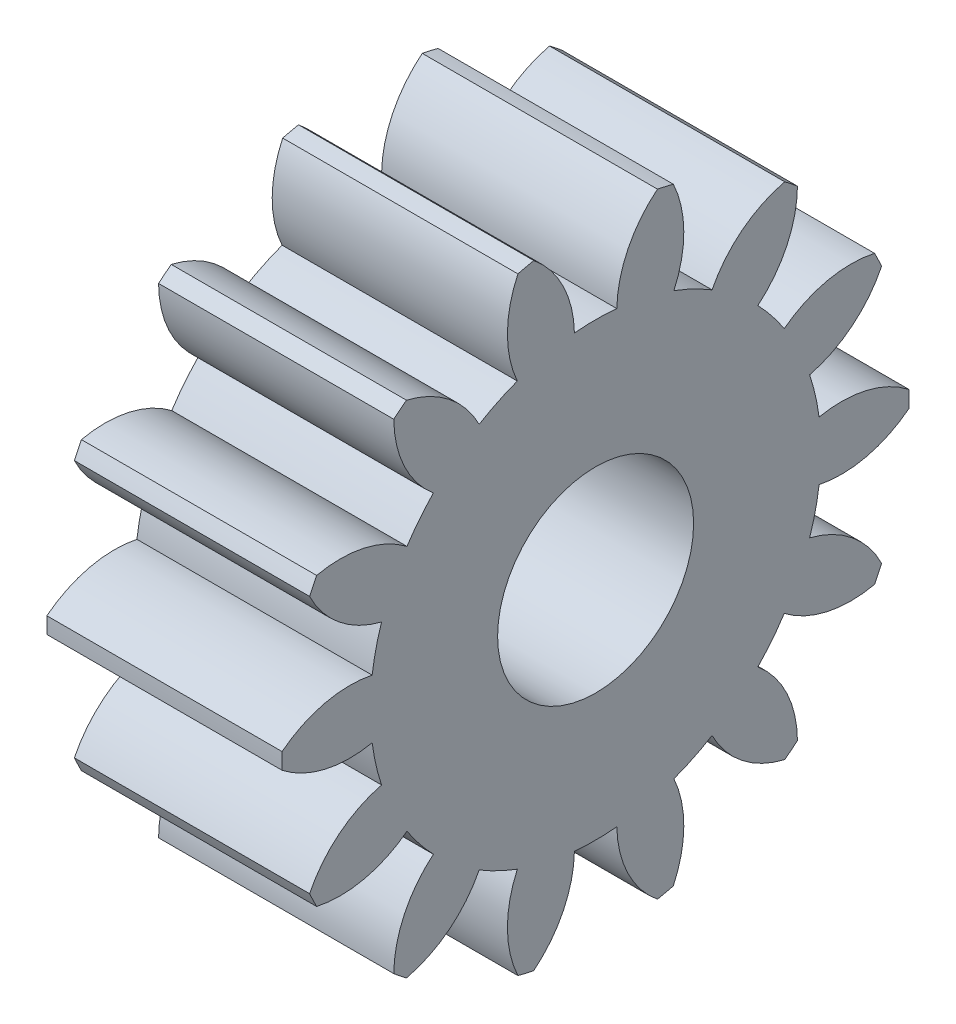
SolidWorks part; units mm, degrees
ref_plane "Plane1" through (0, 0, 0) normal (0, 0, 1) x (1, 0, 0)
ref_plane "Plane2" through (0, 0, 0) normal (0, 1, 0) x (1, 0, 0)
ref_plane "Plane3" through (0, 0, 0) normal (1, 0, 0) x (0, 0, -1)
other "Configuration Table"
sketch "HoldingSke" plane through (0, 0, 0) normal (0, 1, 0) x (1, 0, 0)
  line L0 (0, 0) -> (0.9703, -0.2419)
  line L1 (-15, 0) -> (100, 0) construction
  line L2 (0, 0) -> (-2.1039, 2.3779)
  line L3 (0, 0) -> (-11.863, 4.5341)
  line L4 (0, 0) -> (8.3795, 2.0892)
  line L5 (0, 0) -> (-9.3695, -3.4946)
  line L6 (0, 0) -> (-4.9738, -3.3558)
  line L7 (-2.1039, 2.3779) -> (0.0486, 12.1435)
  line L8 (-76.2, 54.61) -> (-75.3, 54.61)
  line L9 (-71.009, 38.7566) -> (-53.1078, 45.2721)
  line L10 (-76.2, 71.12) -> (104.1128, 71.12)
  line L11 (0, 0) -> (-6, 0)
  line L12 (-76.2, 101.6) -> (-76.162, 101.6)
  line L13 (24.9733, 27.94) -> (52.9518, 28.4284)
  line L14 (24.9733, 27.94) -> (24.9743, 27.94)
  line L15 (24.9733, 27.94) -> (100.4006, 29.5858)
  line L16 (-63.627, -1) -> (-12.827, -1)
  circle A0 centre (0, 0) radius 2.5
  circle A1 centre (0, 0) radius 5.749
  circle A2 centre (0, 0) radius 37.5
  circle A3 centre (0, 0) radius 2.5
  dimension "MHD" = 11.498
  dimension "Hub_dia" = 75
  dimension "Bore" = 5
  dimension "MBD" = 5
  dimension "Num_teeth" = 14
  dimension "Pitch" = 1
  dimension "Overall_len" = 10
  dimension "Show_teeth" = 14
  dimension "Thickness" = 6
  dimension "OAL" = 10.0001
  dimension "T_dim" = 0.9
  dimension "Ap" = 20
  dimension "H" = 19.05
  dimension "Pitch_radius" = 180.3128
  dimension "Width" = 6
  dimension "Backlash" = 0.038
  dimension "Addendum_fac" = 1
  dimension "Dedendum_fac" = 1.25
  dimension "Clearance_fac" = 0.25
  dimension "Dedendum_add" = 0.001
  dimension "Module" = 1
sketch "BasProSke" plane through (0, 0, 0) normal (0, 1, 0) x (1, 0, 0)
  line L0 (-10, 0) -> (60, 0) construction
  line L1 (0, 0) -> (0, 8)
  line L2 (0, 0) -> (6, 0)
  line L3 (6, 0) -> (6, 8)
  line L4 (6, 8) -> (0, 8)
  dimension "Thickness" = 6
  dimension "Diameter" = 16
revolve "Base-Revolve" add sketch "BasProSke" angle 360 about L0
sketch "TooCutSke" plane through (0, 0, 0) normal (1, 0, 0) x (0, 0, -1)
  line L1 (0, 0) -> (0, 107) construction
  line L2 (0, 0) -> (-0.8502, 6.9482) construction
  line L3 (0, 0) -> (-3.0989, 13.5772) construction
  line L4 (-0.8502, 6.9482) -> (-1.5494, 6.7886) construction
  arc A0 (0.5404, 5.7235) -> (-0.5404, 5.7235) centre (0, 0) ccw
  arc A1 (1.6036, 7.8636) -> (-1.6036, 7.8636) centre (0, 0) ccw
  circle A2 centre (0, 0) radius 7 construction
  circle A3 centre (0, 0) radius 6.5778 construction
  arc A4 (-0.5404, 5.7235) -> (-1.6036, 7.8636) centre (-3.3398, 5.6669) ccw
  arc A5 (1.6036, 7.8636) -> (0.5404, 5.7235) centre (3.3398, 5.6669) ccw
  dimension "Root_dia" = 11.498
  dimension "Overcut_dia" = 16.0508
  dimension "Pitch_dia" = 14
  dimension "Base_dia" = 13.1557
  dimension "Flank_rad" = 2.8
  dimension "Half_ang" = 12.857
  dimension "Half_CT" = 0.7173
extrude "ToothCut" cut sketch "TooCutSke" along normal through all
fillet "Breaks" [suppressed] radius 0.02
fillet "RootFillets" [suppressed] radius 0.251
pattern_circular "TeethCuts" count 14 every 25.714 about axis through (-10, 0, 0) along (1, 0, 0) of "ToothCut", "RootFillets", "Breaks"
sketch "HubNeaOneSke" plane through (0, 0, 0) normal (-1, 0, 0) x (0, 0, 1)
  circle A0 centre (0, 0) radius 5.749
  dimension "Diameter" = 11.498
extrude "HubNearOne" [suppressed] add sketch "HubNeaOneSke" along normal blind 4.0001
sketch "HubNeaBotSke" plane through (0, 0, 0) normal (-1, 0, 0) x (0, 0, 1)
  circle A0 centre (0, 0) radius 5.749
  dimension "Diameter" = 11.498
extrude "HubNearBoth" [suppressed] add sketch "HubNeaBotSke" along normal blind 2
ref_plane "FarPln" through (6, 0, 0) normal (1, 0, 0) x (0, 0, -1)
sketch "HubFarSke" plane through (6, 0, 0) normal (1, 0, 0) x (0, 0, -1)
  circle A0 centre (0, 0) radius 5.749
  dimension "Diameter" = 11.498
extrude "HubFar" [suppressed] add sketch "HubFarSke" along normal blind 2
sketch "BorSke" plane through (0, 0, 0) normal (1, 0, 0) x (0, 0, -1)
  circle A0 centre (0, 0) radius 2.5
  dimension "Diameter" = 5
extrude "Bore" cut sketch "BorSke" along normal mid plane 20.0001
sketch "KeySke" plane through (0, 0, 0) normal (1, 0, 0) x (0, 0, -1)
  line L0 (-1, 0) -> (-1, 3.4)
  line L1 (-1, 3.4) -> (1, 3.4)
  line L2 (1, 3.4) -> (1, 0)
  line L3 (0, 0) -> (0, 34) construction
  line L4 (-1, 0) -> (1, 0)
  dimension "Offset" = 3.4
  dimension "Width" = 2
extrude "Keyway" [suppressed] cut sketch "KeySke" along normal mid plane 20.0001
pattern_circular "Keyway2" [suppressed] count 2 every 90 about axis through (-10, 0, 0) along (1, 0, 0)
equation "' \"Module@HoldingSke\" = 6.35"
equation "' \"Num_teeth@HoldingSke\" = 12"
equation "' \"Ap@HoldingSke\" =  20"
equation "' \"Ap@HoldingSke\" = 20"
equation "' \"Width@HoldingSke\" = 0.5 * 25.4"
equation "' \"Hub_dia@HoldingSke\"= 1 * 25.4"
equation "' \"Hub_dia@HoldingSke\" = 1 * 25.4"
equation "' \"Overall_len@HoldingSke\" = 1.0 * 25.4"
equation "' \"Bore@HoldingSke\" = 0.75 * 25.4"
equation "' \"T_dim@HoldingSke\" = 0.1 * 25.4"
equation "' \"Width@KeySke\" = 0.25 * 25.4"
equation "' \"Show_teeth@HoldingSke\" = 13"
equation "' \"Backlash@HoldingSke\" = 0.009 * 25.4"
equation "' \"Addendum_fac@HoldingSke\" = 1.0"
equation "' \"Dedendum_fac@HoldingSke\" = 1.25"
equation "' \"Dedendum_add@HoldingSke\" = 0.00005 * 25.4"
equation "' \"Clearance_fac@HoldingSke\" = 0.25"
equation "\"Pitch@HoldingSke\" = 1 / \"Module@HoldingSke\""
equation "\"Overcut_dia@TooCutSke\" = (\"Num_teeth@HoldingSke\" + 2 * \"Addendum_fac@HoldingSke\") / \"Pitch@HoldingSke\" + 0.002 * 25.4"
equation "\"Pitch_dia@TooCutSke\" = \"Num_teeth@HoldingSke\" / \"Pitch@HoldingSke\""
equation "\"Base_dia@TooCutSke\" = \"Num_teeth@HoldingSke\" / \"Pitch@HoldingSke\" * cos((\"Ap@HoldingSke\"  * 3.14159265 / 180))"
equation "\"Root_dia@TooCutSke\" = (\"Num_teeth@HoldingSke\" + 2) / \"Pitch@HoldingSke\" - 2 * (\"Addendum_fac@HoldingSke\" + \"Dedendum_fac@HoldingSke\") / \"Pitch@HoldingSke\" - \"Dedendum_add@HoldingSke\" * 2"
equation "\"Half_ang@TooCutSke\" = 180 / \"Num_teeth@HoldingSke\""
equation "\"Half_CT@TooCutSke\" = \"Num_teeth@HoldingSke\" / \"Pitch@HoldingSke\" * sin((3.14159265 / 2 / \"Num_teeth@HoldingSke\")) / 2 - 7 * \"Backlash@HoldingSke\" / 4"
equation "\"Flank_rad@TooCutSke\" = \"Num_teeth@HoldingSke\" / \"Pitch@HoldingSke\" / 5"
equation "\"Radius@RootFillets\" = \"Clearance_fac@HoldingSke\" / \"Pitch@HoldingSke\" + \"Dedendum_add@HoldingSke\""
equation "\"Break_rad@Breaks\" = 0.02 / \"Pitch@HoldingSke\""
equation "\"Thickness@HoldingSke\" = \"Width@HoldingSke\""
equation "\"OAL@HoldingSke\" = \"Thickness@HoldingSke\""
equation "\"MHD@HoldingSke\" = (\"Num_teeth@HoldingSke\" + 2) / \"Pitch@HoldingSke\" - 2 * (\"Addendum_fac@HoldingSke\" + \"Dedendum_fac@HoldingSke\")  / \"Pitch@HoldingSke\" - \"Dedendum_add@HoldingSke\" * 2"
equation "\"MBD@HoldingSke\" = (\"Num_teeth@HoldingSke\" + 2) / \"Pitch@HoldingSke\" - 2 * (\"Addendum_fac@HoldingSke\" + \"Dedendum_fac@HoldingSke\")  / \"Pitch@HoldingSke\" - \"Dedendum_add@HoldingSke\" * 2 - 0.002 * 25.4"
equation "\"MHD@HoldingSke\" = ((sgn( \"MHD@HoldingSke\" - \"Hub_dia@HoldingSke\" )-1)*( \"MHD@HoldingSke\" - \"Hub_dia@HoldingSke\" ))/-2+ \"Hub_dia@HoldingSke\""
equation "\"MBD@HoldingSke\" = ((sgn( \"MBD@HoldingSke\" - \"Bore@HoldingSke\" )-1)*( \"MBD@HoldingSke\" - \"Bore@HoldingSke\" ))/-2+ \"Bore@HoldingSke\""
equation "\"OAL@HoldingSke\" = ((sgn( \"OAL@HoldingSke\" - \"Overall_len@HoldingSke\" )+1)*( \"OAL@HoldingSke\" - \"Overall_len@HoldingSke\" ))/2 + \"Overall_len@HoldingSke\" + 0.000002 * 25.4"
equation "\"Num_teeth@TeethCuts\" = int( \"Show_teeth@HoldingSke\" ) + 1"
equation "\"Num_teeth@TeethCuts\" = ((sgn( \"Num_teeth@TeethCuts\" - \"Num_teeth@HoldingSke\" )-1)*( \"Num_teeth@TeethCuts\" - \"Num_teeth@HoldingSke\" ))/-2+ \"Num_teeth@HoldingSke\""
equation "\"Num_teeth@TeethCuts\" = ((sgn( \"Num_teeth@TeethCuts\" - 2.0)+1)*( \"Num_teeth@TeethCuts\" - 2.0))/2 +2.0"
equation "\"Angle@TeethCuts\" = 360.0 / \"Num_teeth@HoldingSke\""
equation "\"Diameter@BasProSke\" = (\"Num_teeth@HoldingSke\" + 2 * \"Addendum_fac@HoldingSke\") / \"Pitch@HoldingSke\""
equation "\"Thickness@BasProSke\"  = \"Thickness@HoldingSke\""
equation "' \"Fillet_rad@BasProSke\" =  \"Thickness@HoldingSke\" * 0.05"
equation "' \"Fillet_rad@BasProSke\" = \"Thickness@HoldingSke\" * 0.05"
equation "\"MHD@HoldingSke\" = ((sgn( \"MHD@HoldingSke\" - \"Root_dia@TooCutSke\" )-1)*( \"MHD@HoldingSke\" - \"Root_dia@TooCutSke\" ))/-2+ \"Root_dia@TooCutSke\""
equation "\"Diameter@HubNeaOneSke\" = \"MHD@HoldingSke\""
equation "\"Length@HubNearOne\" = \"OAL@HoldingSke\" - \"Thickness@BasProSke\""
equation "\"Diameter@HubNeaBotSke\" = \"MHD@HoldingSke\""
equation "\"Length@HubNearBoth\" = ( \"OAL@HoldingSke\" - \"Thickness@BasProSke\" ) / 2.0"
equation "\"Thickness@FarPln\" = \"Thickness@BasProSke\""
equation "\"Diameter@HubFarSke\" = \"MHD@HoldingSke\""
equation "\"Length@HubFar\" = ( \"OAL@HoldingSke\" - \"Thickness@BasProSke\" ) / 2.0"
equation "\"Diameter@BorSke\" = \"MBD@HoldingSke\""
equation "\"D1@Bore\" = \"OAL@HoldingSke\" * 2.0"
equation "\"D1@Keyway\" = \"OAL@HoldingSke\" * 2.0"
equation "\"Offset@KeySke\" = \"T_dim@HoldingSke\" + \"MBD@HoldingSke\" / 2.0"
